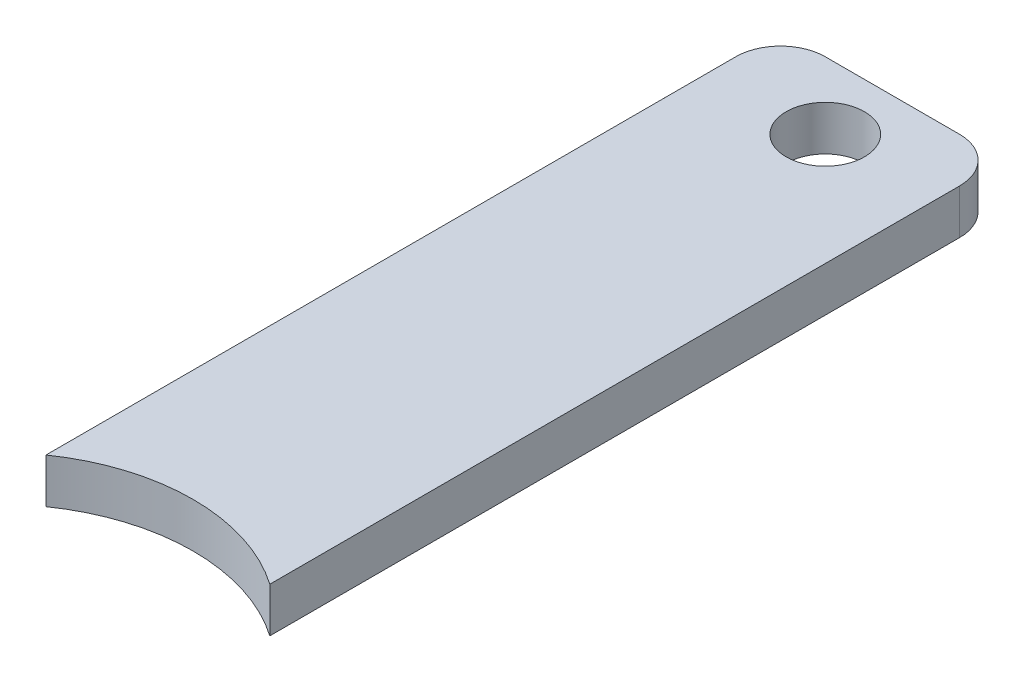
SolidWorks part; units mm, degrees
material "ASTM A36 Steel"
ref_plane "Front Plane" through (0, 0, 0) normal (0, 0, 1) x (1, 0, 0)
ref_plane "Top Plane" through (0, 0, 0) normal (0, 1, 0) x (1, 0, 0)
ref_plane "Right Plane" through (0, 0, 0) normal (1, 0, 0) x (0, 0, -1)
sketch "Sketch1" plane through (0, 0, 0) normal (0, 1, 0) x (1, 0, 0)
  line L1 (-10, 14.3614) -> (-10, 76)
  line L2 (10, 14.3614) -> (10, 76)
  line L3 (6, 80) -> (-6, 80)
  arc A0 (10, 14.3614) -> (-10, 14.3614) centre (0, 0) ccw
  circle A1 centre (0, 74) radius 3.5
  arc A2 (10, 76) -> (6, 80) centre (6, 76) ccw
  arc A3 (-10, 76) -> (-6, 80) centre (-6, 76) cw
  dimension "D1" = 35
  dimension "D2" = 7
  dimension "D3" = 6
  dimension "D4" = 4
extrude "Boss-Extrude1" add sketch "Sketch1" along normal blind 4
